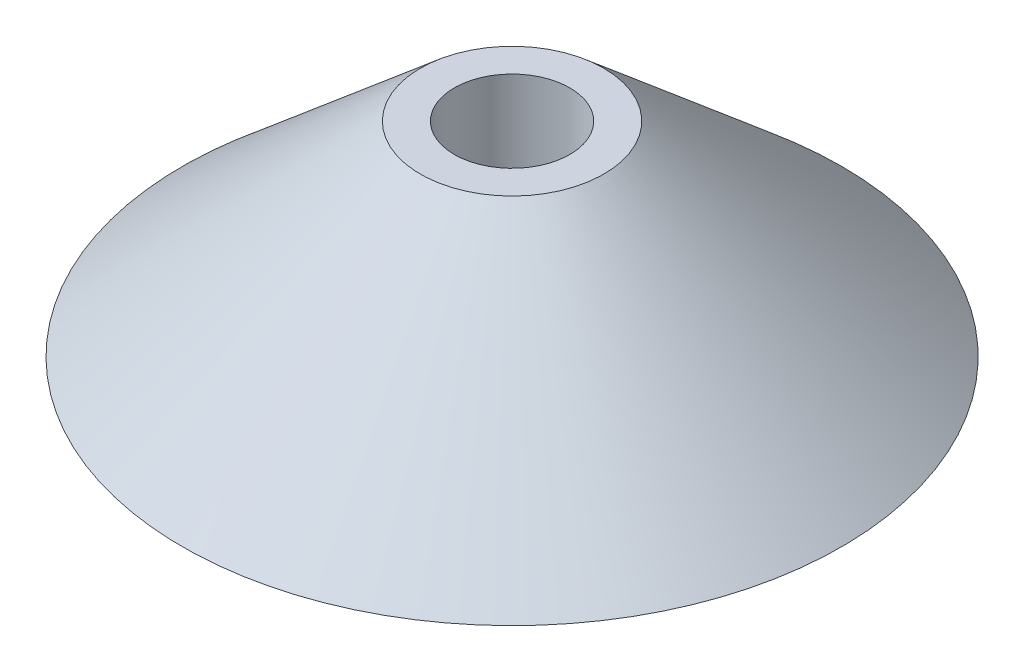
SolidWorks part; units mm, degrees
ref_plane "Ebene vorne" through (0, 0, 0) normal (0, 0, 1) x (1, 0, 0)
ref_plane "Ebene oben" through (0, 0, 0) normal (0, 1, 0) x (1, 0, 0)
ref_plane "Ebene rechts" through (0, 0, 0) normal (1, 0, 0) x (0, 0, -1)
sketch "Sketch1" plane through (0, 0, 0) normal (0, 0, 1) x (1, 0, 0)
  line L0 (0, 11.3265) -> (0, -9.4898) construction
  line L2 (-2.7, 6) -> (-9.7, 0)
  line L3 (-9.7, 0) -> (-1.7, 0)
  line L4 (-2.7, 6) -> (-1.7, 6)
  line L5 (-1.7, 6) -> (-1.7, 0)
  dimension "D1" = 6
  dimension "D2" = 1
  dimension "D3" = 3.4
  dimension "D4" = 8
revolve "Revolve1" add sketch "Sketch1" angle 360 about L0
